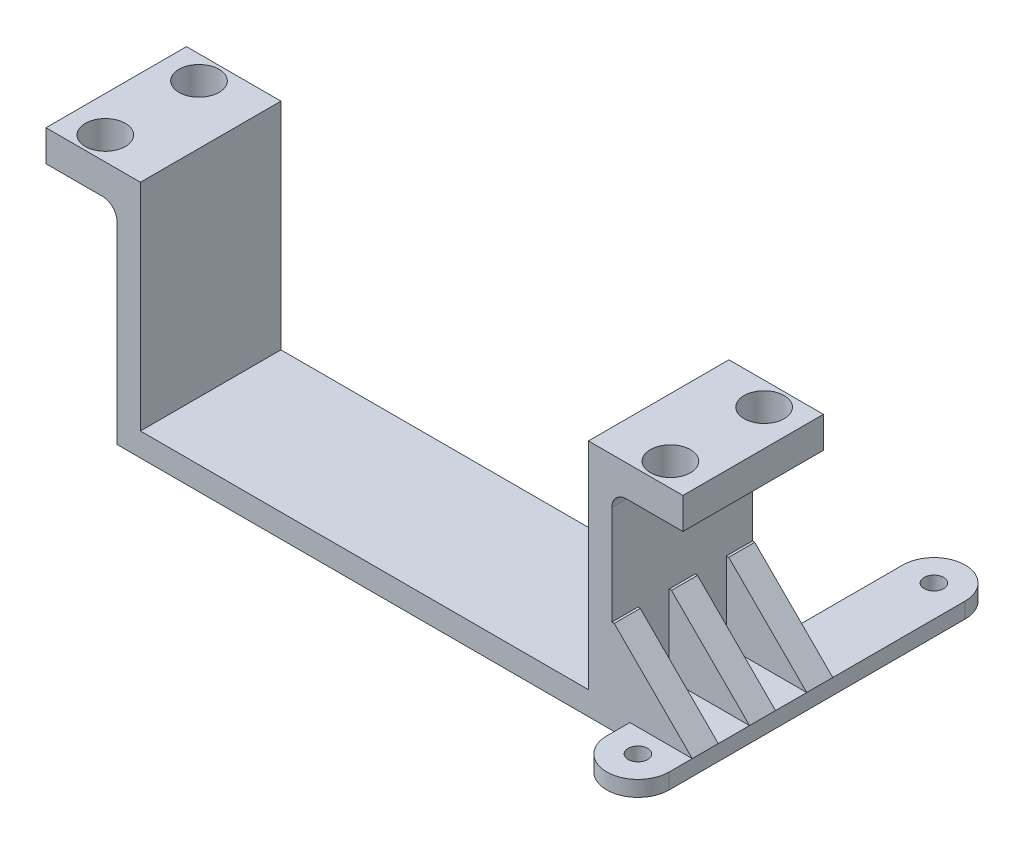
SolidWorks part; units mm, degrees
ref_plane "Front Plane" through (0, 0, 0) normal (0, 0, 1) x (1, 0, 0)
ref_plane "Top Plane" through (0, 0, 0) normal (0, 1, 0) x (1, 0, 0)
ref_plane "Right Plane" through (0, 0, 0) normal (1, 0, 0) x (0, 0, -1)
sketch "Sketch1" plane through (0, 0, 0) normal (0, 0, 1) x (1, 0, 0)
  line L0 (-3.81, 35.052) -> (0, 35.052)
  line L1 (0, 0) -> (72.898, 0)
  line L2 (0, 0) -> (0, 35.052)
  line L4 (72.898, 0) -> (72.898, 35.052)
  line L6 (-3.81, 35.052) -> (-3.81, -3.81)
  line L7 (-3.81, -3.81) -> (76.708, -3.81)
  line L8 (76.708, 35.052) -> (76.708, -3.81)
  line L9 (72.898, 35.052) -> (76.708, 35.052)
  dimension "D1" = 3.81
  dimension "D2" = 3.81
  dimension "D3" = 3.81
  dimension "D4" = 38.862
  dimension "D5" = 72.898
extrude "Boss-Extrude1" add sketch "Sketch1" along normal blind 22.86
sketch "Sketch2" plane through (0, -3.81, 0) normal (0, -1, 0) x (1, 0, 0)
  line L0 (84.709, 26.6192) -> (84.709, -21.5392) construction
  line L2 (79.629, 26.6192) -> (79.629, 22.86)
  line L3 (89.789, 26.6192) -> (89.789, -21.5392)
  line L4 (-3.81, 22.86) -> (76.708, 22.86) construction
  line L5 (76.708, 22.86) -> (76.708, 0) construction
  line L6 (76.708, 22.86) -> (79.629, 22.86)
  line L7 (76.708, 22.86) -> (76.708, 0)
  line L8 (76.708, 0) -> (79.629, 0)
  line L9 (79.629, 0) -> (79.629, -21.5392)
  circle A0 centre (84.709, 26.6192) radius 1.5875
  circle A1 centre (84.709, -21.5392) radius 1.5875
  arc A2 (89.789, 26.6192) -> (79.629, 26.6192) centre (84.709, 26.6192) ccw
  arc A3 (79.629, -21.5392) -> (89.789, -21.5392) centre (84.709, -21.5392) ccw
  point P4 (84.709, 2.54)
  point P5 (76.708, 11.43)
  point P6 (36.449, 22.86)
  point P9 (84.709, 25.0317)
  point P14 (84.709, -19.9517)
  point P15 (0, 0)
  point P22 (77.089, 22.86)
  dimension "D2" = 3.175
  dimension "D3" = 5.08
  dimension "D1" = 44.9834
  dimension "D4" = 48.26
  dimension "D5" = 8.89
extrude "Boss-Extrude2" add sketch "Sketch2" against normal blind 2.54 contours L2 A3 L3 A2
sketch "Sketch4" plane through (0, 35.052, 0) normal (0, 1, 0) x (1, 0, 0)
  line L0 (0, -22.86) -> (-3.81, -22.86) construction
  line L1 (0, 0) -> (-15.367, 0)
  line L2 (0, 0) -> (0, -22.86)
  line L3 (0, -22.86) -> (-15.367, -22.86)
  line L4 (-15.367, 0) -> (-15.367, -22.86)
  line L5 (-3.81, -22.86) -> (-3.81, 0) construction
  line L6 (-9.525, -3.81) -> (-9.525, -19.05) construction
  circle A0 centre (-9.525, -3.81) radius 3.2639
  circle A1 centre (-9.525, -19.05) radius 3.2639
  point P13 (-15.367, -11.43)
  point P14 (-9.525, -11.43)
  dimension "D1" = 6.5278
  dimension "D2" = 5.715
  dimension "D3" = 7.62
  dimension "D4" = 5.842
extrude "Boss-Extrude3" add sketch "Sketch4" against normal blind 5.08
ref_plane "Plane1" through (36.449, 0, 0) normal (1, 0, 0) x (0, 0, -1)
mirror "Mirror1" about plane through (36.449, 0, 0) normal (1, 0, 0) of "Boss-Extrude3"
sketch "Sketch5" plane through (0, -1.27, 0) normal (0, 1, 0) x (1, 0, 0)
  line L0 (89.789, 21.5392) -> (89.789, -26.6192) construction
  line L1 (76.708, 0) -> (89.789, 0)
  line L2 (76.708, 0) -> (76.708, -4.2333)
  line L3 (76.708, -4.2333) -> (89.789, -4.2333)
  line L4 (89.789, 0) -> (89.789, -4.2333)
  line L5 (76.708, -22.86) -> (76.708, 0) construction
  line L6 (76.708, -22.86) -> (89.789, -22.86)
  line L7 (76.708, -22.86) -> (76.708, -18.6267)
  line L8 (76.708, -18.6267) -> (89.789, -18.6267)
  line L9 (89.789, -22.86) -> (89.789, -18.6267)
  line L10 (76.708, -9.3133) -> (89.789, -9.3133)
  line L11 (76.708, -9.3133) -> (76.708, -13.5467)
  line L12 (76.708, -13.5467) -> (89.789, -13.5467)
  line L13 (89.789, -9.3133) -> (89.789, -13.5467)
  dimension "D1" = 5.08
  dimension "D2" = 5.08
extrude "Boss-Extrude4" add sketch "Sketch5" along normal blind 12.7
chamfer "Chamfer1" distance 12.7 angle 45 3 edges at (89.789, 11.43, 20.7433) (89.789, 11.43, 11.43) (89.789, 11.43, 2.1167)
fillet "Fillet1" radius 2.38 2 edges at (76.708, 29.972, 11.43) (-3.81, 29.972, 11.43)
